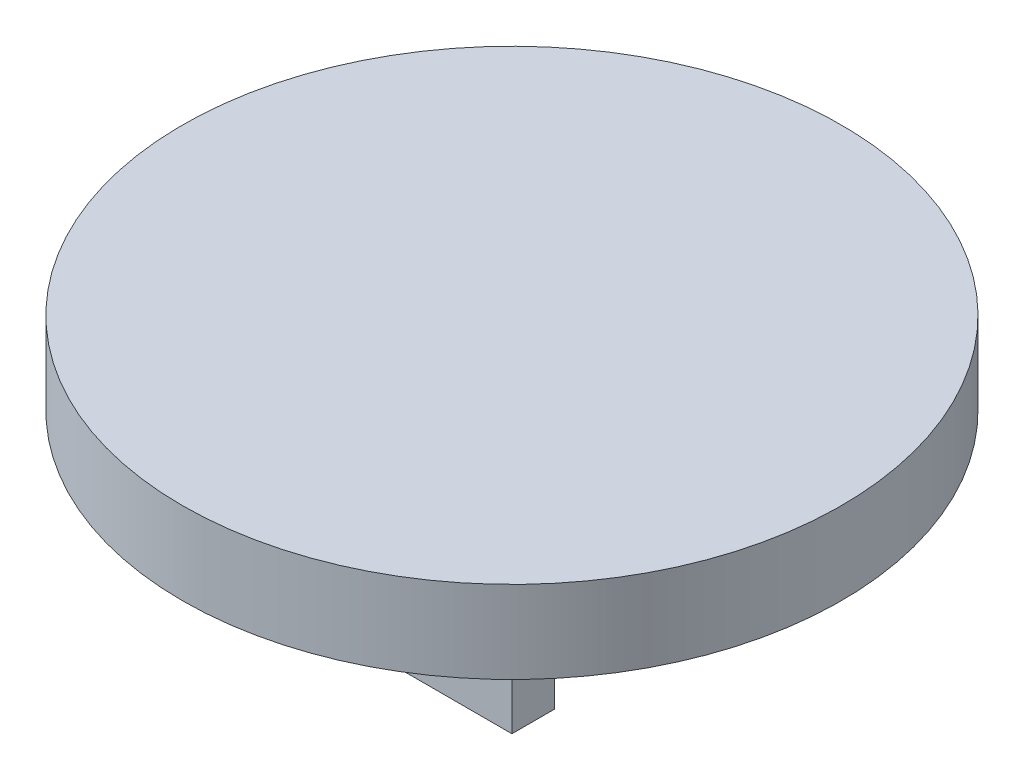
SolidWorks part; units mm, degrees
ref_plane "Front Plane" through (0, 0, 0) normal (0, 0, 1) x (1, 0, 0)
ref_plane "Top Plane" through (0, 0, 0) normal (0, 1, 0) x (1, 0, 0)
ref_plane "Right Plane" through (0, 0, 0) normal (1, 0, 0) x (0, 0, -1)
sketch "Sketch1" plane through (0, 0, 0) normal (0, 1, 0) x (1, 0, 0)
  circle A0 centre (0, 0) radius 12
extrude "Boss-Extrude1" add sketch "Sketch1" along normal blind 3
sketch "Sketch3" plane through (0, 0, 0) normal (0, -1, 0) x (1, 0, 0)
  line L1 (-5, 5) -> (5, 5)
  line L2 (-5, 5) -> (-5, -5)
  line L3 (-5, -5) -> (5, -5)
  line L4 (5, 5) -> (5, -5)
  line L5 (-5, 5) -> (5, -5) construction
  line L6 (-5, -5) -> (5, 5) construction
  point P0 (0, 0)
  dimension "D1" = 10
  dimension "D2" = 10
extrude "Boss-Extrude3" add sketch "Sketch3" along normal blind 3
sketch "Sketch4" plane through (0, 0, -5) normal (0, 0, -1) x (-1, 0, 0)
  circle A0 centre (0, -1.5) radius 0.5
extrude "Cut-Extrude1" cut sketch "Sketch4" against normal blind 9
sketch "Sketch5" plane through (5, 0, 0) normal (1, 0, 0) x (0, 0, -1)
  line L0 (-1.8114, -3) -> (1.8114, -3)
  line L1 (5, -3) -> (-5, -3) construction
  line L2 (5, 0) -> (-5, 0) construction
  line L3 (-1.8114, -3) -> (1.8114, -3)
  line L4 (-1.8114, -3) -> (-1.8114, 0)
  line L5 (-1.8114, 0) -> (1.8114, 0)
  line L6 (1.8114, -3) -> (1.8114, 0)
  point P5 (0, -3)
  line M1 (5, 0) -> (-5, 0)
  line M3 (-5, -3) -> (5, -3)
extrude "Cut-Extrude2" cut sketch "Sketch5" against normal blind 9 contours L6 L4 M3 M1
sketch "Sketch6" plane through (0, 0, -5) normal (0, 0, -1) x (-1, 0, 0)
  line L1 (-5, 0) -> (2.3767, 0)
  line L2 (-5, 0) -> (-5, -5.1952)
  line L3 (-5, -5.1952) -> (2.3767, -5.1952)
  line L4 (2.3767, 0) -> (2.3767, -5.1952)
extrude "Boss-Extrude5" add sketch "Sketch6" against normal up to surface (10 mm away) up to face at (0, -1.5, 5)
sketch "Sketch7" plane through (0, 0, 5) normal (0, 0, 1) x (1, 0, 0)
  circle A0 centre (0, -3.0725) radius 0.5
extrude "Cut-Extrude3" cut sketch "Sketch7" against normal blind 14
sketch "Sketch8" plane through (-5, 0, 0) normal (-1, 0, 0) x (0, 0, 1)
  line L0 (-1.8869, -5.1952) -> (1.8869, -5.1952)
  line L1 (5, -5.1952) -> (-5, -5.1952) construction
  line L4 (-1.8869, -5.1952) -> (-1.8869, -0.7076)
  line L5 (-1.8869, -0.7076) -> (1.8869, -0.7076)
  line L6 (1.8869, -5.1952) -> (1.8869, -0.7076)
  point P5 (0, -5.1952)
extrude "Cut-Extrude4" cut sketch "Sketch8" against normal through all
sketch "Sketch9" plane through (0, -5.1952, 0) normal (0, -1, 0) x (1, 0, 0)
  line L0 (-5, -1.8869) -> (-5, -5) construction
  line L1 (5, 3.4434) -> (-5, 3.4434)
  line L2 (5, 3.4434) -> (5, -3.4434)
  line L3 (5, -3.4434) -> (-5, -3.4434)
  line L4 (-5, 3.4434) -> (-5, -3.4434)
  line L5 (5, 3.4434) -> (-5, -3.4434) construction
  line L6 (5, -3.4434) -> (-5, 3.4434) construction
  point P0 (0, 0)
extrude "Cut-Extrude5" cut sketch "Sketch9" against normal blind 5
